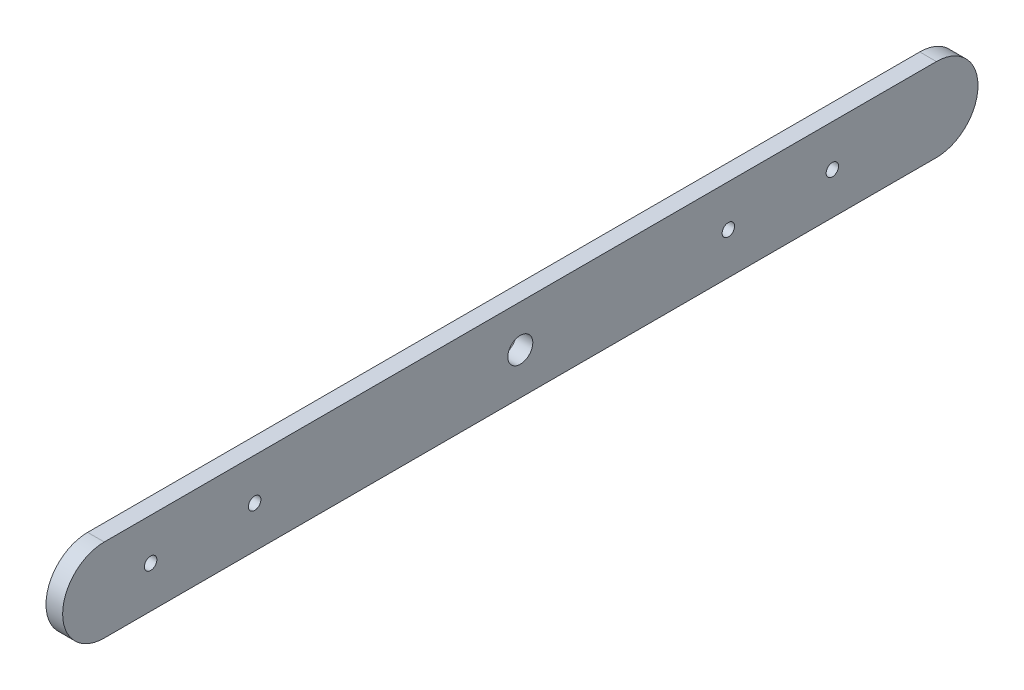
SolidWorks part; units mm, degrees
ref_plane "Alzado" through (0, 0, 0) normal (0, 0, 1) x (1, 0, 0)
ref_plane "Planta" through (0, 0, 0) normal (0, 1, 0) x (1, 0, 0)
ref_plane "Vista lateral" through (0, 0, 0) normal (1, 0, 0) x (0, 0, -1)
sketch "Croquis1" plane through (0, 0, 0) normal (1, 0, 0) x (0, 0, -1)
  line L0 (0, 0) -> (-104.0553, 0)
  line L1 (0, 0) -> (95.9447, 0)
  line L2 (0, 20) -> (95.9447, 20)
  line L3 (0, 20) -> (-104.0553, 20)
  line L4 (-104.0553, 10) -> (-1.0553, 10) construction
  line L5 (95.9447, 10) -> (-7.0553, 10) construction
  arc A0 (-104.0553, 0) -> (-104.0553, 20) centre (-104.0553, 10) cw
  arc A1 (95.9447, 0) -> (95.9447, 20) centre (95.9447, 10) ccw
  circle A4 centre (-4.0553, 10) radius 3
  dimension "D6" = 6
  dimension "D1" = 20
  dimension "D2" = 200
  dimension "D3" = 180
extrude "Saliente-Extruir1" add sketch "Croquis1" along normal blind 4
sketch "Croquis5" plane through (0, 0, 0) normal (-1, 0, 0) x (0, 0, 1)
  line L0 (4.0553, 10) -> (-105.9447, 10) construction
  line L1 (4.0553, 10) -> (4.0553, 20) construction
  line L2 (-95.9447, 20) -> (104.0553, 20) construction
  line L3 (4.0553, 10) -> (67.9053, 10) construction
  line L4 (67.9053, 10) -> (92.9053, 10) construction
  arc A0 (-95.9447, 20) -> (-95.9447, 0) centre (-95.9447, 10) ccw construction
  circle A1 centre (-70.9447, 10) radius 1.5
  circle A2 centre (-45.9447, 10) radius 1.5
  circle A3 centre (67.9053, 10) radius 1.5
  circle A4 centre (92.9053, 10) radius 1.5
  dimension "D1" = 3
  dimension "D2" = 3
  dimension "D3" = 25
  dimension "D4" = 25
  dimension "D5" = 63.85
  dimension "D6" = 88.85
extrude "Cortar-Extruir4" cut sketch "Croquis5" against normal blind 65
